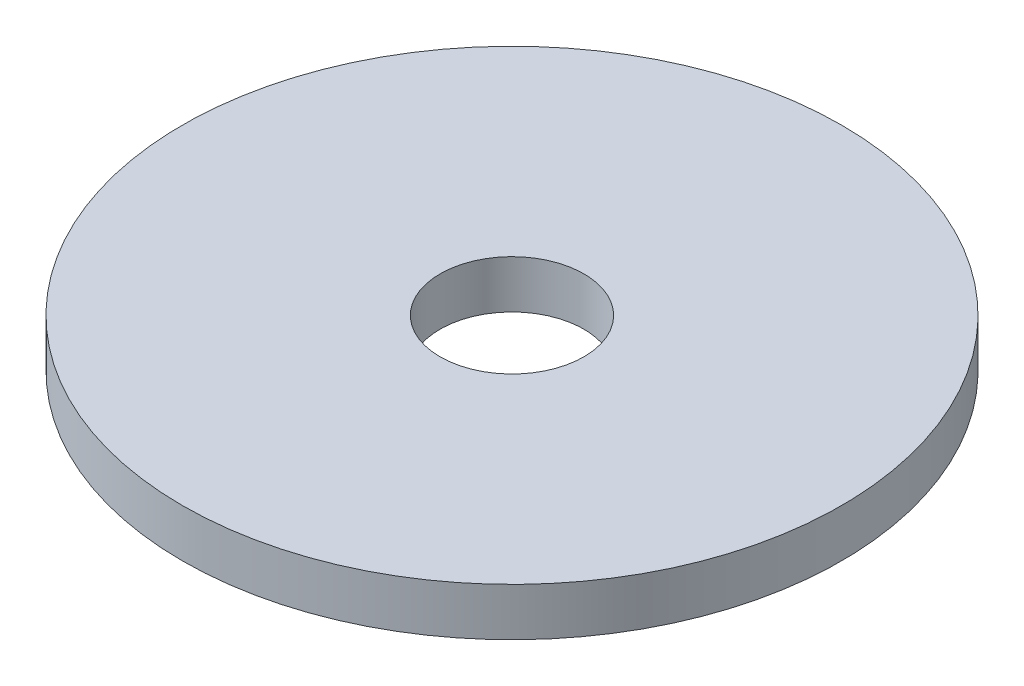
SolidWorks part; units mm, degrees
ref_plane "Front Plane" through (0, 0, 0) normal (0, 0, 1) x (1, 0, 0)
ref_plane "Top Plane" through (0, 0, 0) normal (0, 1, 0) x (1, 0, 0)
ref_plane "Right Plane" through (0, 0, 0) normal (1, 0, 0) x (0, 0, -1)
sketch "Sketch1" plane through (0, 0, 0) normal (0, 1, 0) x (1, 0, 0)
  circle A0 centre (0, 0) radius 27.5
  circle A1 centre (0, 0) radius 6
  dimension "D1" = 55
  dimension "D2" = 12
extrude "Boss-Extrude1" add sketch "Sketch1" along normal blind 4
sketch "Sketch2" plane through (0, 0, 0) normal (0, -1, 0) x (1, 0, 0)
  spline S0 degree 3 poles (783.5995, -748.4495) (32.8431, -47.3253) (88.3902, -17.4198) (93.8115, -26.7138) (93.9859, -27.5176) (93.9069, -28.333) (93.5786, -29.0907) (93.0307, -29.7103) (92.3264, -30.1263) (91.5328, -30.3082) (80.8051, -29.3947) (82.7854, 34.349) (1055.4923, -290.1326) knots -0.028735 -0.028735 -0.028735 -0.028735 0.000809 0.001618 0.002427 0.003235 0.004044 0.004853 0.005662 0.006471 0.00728 0.037205 0.037205 0.037205 0.037205 weights 1 1 1 1 1 1 1 1 1 1 1 1 1 only from (92.7348, -25.473) to (89.9615, -29.8717) construction
  spline S1 degree 3 poles (-600.9031, 693.1047) (149.8533, -8.0194) (94.3062, -37.925) (88.8848, -28.631) (88.7105, -27.8272) (88.7895, -27.0118) (89.1177, -26.254) (89.6657, -25.6344) (90.37, -25.2184) (91.1635, -25.0366) (101.8913, -25.95) (99.911, -89.6937) (-872.7959, 234.7879) knots -0.028735 -0.028735 -0.028735 -0.028735 0.000809 0.001618 0.002427 0.003235 0.004044 0.004853 0.005662 0.006471 0.00728 0.037205 0.037205 0.037205 0.037205 weights 1 1 1 1 1 1 1 1 1 1 1 1 1 only from (89.9615, -29.8717) to (92.7348, -25.473) construction
  spline S2 degree 3 poles (791.8718, -750.5841) (24.3799, -66.7142) (78.4052, -37.6563) (83.7379, -46.8377) (83.9102, -47.6464) (83.8268, -48.4628) (83.4968, -49.2142) (82.9576, -49.8227) (82.2624, -50.2396) (81.4531, -50.4267) (70.9451, -49.5095) (71.5543, 11.7618) (1054.8388, -272.393) knots -0.028153 -0.028153 -0.028153 -0.028153 0.000809 0.001618 0.002426 0.003235 0.004044 0.004853 0.005662 0.006471 0.007279 0.036703 0.036703 0.036703 0.036703 weights 1 1 1 1 1 1 1 1 1 1 1 1 1 only from (82.6582, -45.5904) to (79.8848, -49.9891) construction
  spline S3 degree 3 poles (-629.3288, 655.0045) (138.1631, -28.8654) (84.1378, -57.9233) (78.8051, -48.7419) (78.6328, -47.9332) (78.7162, -47.1167) (79.0462, -46.3654) (79.5854, -45.7569) (80.2806, -45.34) (81.0899, -45.1529) (91.5979, -46.0701) (90.9887, -107.3414) (-892.2958, 176.8135) knots -0.028153 -0.028153 -0.028153 -0.028153 0.000809 0.001618 0.002426 0.003235 0.004044 0.004853 0.005662 0.006471 0.007279 0.036703 0.036703 0.036703 0.036703 weights 1 1 1 1 1 1 1 1 1 1 1 1 1 only from (79.8848, -49.9891) to (82.6582, -45.5904) construction
  spline S4 degree 3 poles (-598.596, 654.2019) (152.1604, -46.9222) (96.6134, -76.8278) (91.192, -67.5338) (91.0177, -66.73) (91.0967, -65.9146) (91.4249, -65.1568) (91.9729, -64.5372) (92.6772, -64.1212) (93.4707, -63.9394) (104.1984, -64.8528) (102.2181, -128.5965) (-870.4887, 195.8851) knots -0.028735 -0.028735 -0.028735 -0.028735 0.000809 0.001618 0.002427 0.003235 0.004044 0.004853 0.005662 0.006471 0.00728 0.037205 0.037205 0.037205 0.037205 weights 1 1 1 1 1 1 1 1 1 1 1 1 1 only from (92.2687, -68.7745) to (95.042, -64.3758) construction
  spline S5 degree 3 poles (785.9067, -787.3522) (35.1503, -86.2281) (90.6973, -56.3225) (96.1187, -65.6166) (96.2931, -66.4204) (96.214, -67.2358) (95.8858, -67.9935) (95.3378, -68.6131) (94.6335, -69.0291) (93.84, -69.211) (83.1123, -68.2975) (85.0926, -4.5538) (1057.7994, -329.0354) knots -0.028735 -0.028735 -0.028735 -0.028735 0.000809 0.001618 0.002427 0.003235 0.004044 0.004853 0.005662 0.006471 0.00728 0.037205 0.037205 0.037205 0.037205 weights 1 1 1 1 1 1 1 1 1 1 1 1 1 only from (95.042, -64.3758) to (92.2687, -68.7745) construction
  spline S6 degree 3 poles (805.7524, -788.5108) (55.2705, -87.2378) (112.9894, -54.729) (118.579, -64.2831) (118.7534, -65.0889) (118.6754, -65.9009) (118.3456, -66.6633) (117.797, -67.2821) (117.0927, -67.6976) (116.2996, -67.8789) (105.571, -66.9633) (107.474, -3.1589) (1081.3265, -323.7381) knots -0.0296 -0.0296 -0.0296 -0.0296 0.000809 0.001618 0.002426 0.003235 0.004044 0.004853 0.005662 0.00647 0.007279 0.037234 0.037234 0.037234 0.037234 weights 1 1 1 1 1 1 1 1 1 1 1 1 1 only from (117.5026, -63.0438) to (114.7292, -67.4425) construction
  spline S7 degree 3 poles (-573.5206, 658.0246) (176.9613, -43.2484) (119.2424, -75.7573) (113.6527, -66.2031) (113.4784, -65.3973) (113.5564, -64.5854) (113.8861, -63.8229) (114.4348, -63.2041) (115.1391, -62.7886) (115.9322, -62.6073) (126.6608, -63.5229) (124.7578, -127.3273) (-849.0948, 193.2519) knots -0.0296 -0.0296 -0.0296 -0.0296 0.000809 0.001618 0.002426 0.003235 0.004044 0.004853 0.005662 0.00647 0.007279 0.037234 0.037234 0.037234 0.037234 weights 1 1 1 1 1 1 1 1 1 1 1 1 1 only from (114.7292, -67.4425) to (117.5026, -63.0438) construction
  spline S8 degree 3 poles (-566.0587, 675.6514) (184.6977, -25.4728) (129.1506, -55.3783) (123.7292, -46.0843) (123.5549, -45.2805) (123.6339, -44.4651) (123.9621, -43.7073) (124.5101, -43.0877) (125.2144, -42.6717) (126.0079, -42.4899) (136.7357, -43.4034) (134.7553, -107.147) (-837.9515, 217.3346) knots -0.028735 -0.028735 -0.028735 -0.028735 0.000809 0.001618 0.002427 0.003235 0.004044 0.004853 0.005662 0.006471 0.00728 0.037205 0.037205 0.037205 0.037205 weights 1 1 1 1 1 1 1 1 1 1 1 1 1 only from (124.8059, -47.325) to (127.5792, -42.9263) construction
  spline S9 degree 3 poles (818.4439, -765.9028) (67.6875, -64.7786) (123.2345, -34.8731) (128.6559, -44.1671) (128.8303, -44.9709) (128.7513, -45.7863) (128.423, -46.544) (127.8751, -47.1636) (127.1708, -47.5797) (126.3772, -47.7615) (115.6495, -46.848) (117.6298, 16.8956) (1090.3367, -307.5859) knots -0.028735 -0.028735 -0.028735 -0.028735 0.000809 0.001618 0.002427 0.003235 0.004044 0.004853 0.005662 0.006471 0.00728 0.037205 0.037205 0.037205 0.037205 weights 1 1 1 1 1 1 1 1 1 1 1 1 1 only from (127.5792, -42.9263) to (124.8059, -47.325) construction
  spline S10 degree 3 poles (-578.4426, 694.4368) (172.3138, -6.6874) (116.7667, -36.5929) (111.3453, -27.2989) (111.171, -26.4951) (111.25, -25.6797) (111.5783, -24.922) (112.1262, -24.3024) (112.8305, -23.8864) (113.6241, -23.7045) (124.3518, -24.618) (122.3715, -88.3617) (-850.3354, 236.1199) knots -0.028735 -0.028735 -0.028735 -0.028735 0.000809 0.001618 0.002427 0.003235 0.004044 0.004853 0.005662 0.006471 0.00728 0.037205 0.037205 0.037205 0.037205 weights 1 1 1 1 1 1 1 1 1 1 1 1 1 only from (112.422, -28.5397) to (115.1954, -24.141) construction
  spline S11 degree 3 poles (806.06, -747.1174) (55.3036, -45.9933) (110.8507, -16.0877) (116.2721, -25.3817) (116.4464, -26.1855) (116.3674, -27.0009) (116.0392, -27.7587) (115.4912, -28.3783) (114.7869, -28.7943) (113.9933, -28.9761) (103.2656, -28.0627) (105.2459, 35.681) (1077.9528, -288.8006) knots -0.028735 -0.028735 -0.028735 -0.028735 0.000809 0.001618 0.002427 0.003235 0.004044 0.004853 0.005662 0.006471 0.00728 0.037205 0.037205 0.037205 0.037205 weights 1 1 1 1 1 1 1 1 1 1 1 1 1 only from (115.1954, -24.141) to (112.422, -28.5397) construction
  spline S12 degree 3 poles (92.7348, -25.473) (92.9652, -25.6182) (93.3894, -25.9901) (93.8115, -26.7138) (93.9859, -27.5176) (93.9069, -28.333) (93.5786, -29.0907) (93.0307, -29.7103) (92.3264, -30.1263) (91.5328, -30.3082) (90.7075, -30.2379) (90.1918, -30.0169) (89.9615, -29.8717) knots 0 0 0 0 0.000809 0.001618 0.002427 0.003235 0.004044 0.004853 0.005662 0.006471 0.00728 0.008088 0.008088 0.008088 0.008088 weights 1 1 1 1 1 1 1 1 1 1 1 1 1
  spline S13 degree 3 poles (89.9615, -29.8717) (89.7312, -29.7265) (89.307, -29.3547) (88.8848, -28.631) (88.7105, -27.8272) (88.7895, -27.0118) (89.1177, -26.254) (89.6657, -25.6344) (90.37, -25.2184) (91.1635, -25.0366) (91.9888, -25.1068) (92.5045, -25.3278) (92.7348, -25.473) knots 0 0 0 0 0.000809 0.001618 0.002427 0.003235 0.004044 0.004853 0.005662 0.006471 0.00728 0.008088 0.008088 0.008088 0.008088 weights 1 1 1 1 1 1 1 1 1 1 1 1 1
  spline S14 degree 3 poles (82.6582, -45.5904) (82.8885, -45.7357) (83.3148, -46.1092) (83.7379, -46.8377) (83.9102, -47.6464) (83.8268, -48.4628) (83.4968, -49.2142) (82.9576, -49.8227) (82.2624, -50.2396) (81.4531, -50.4267) (80.6317, -50.355) (80.1151, -50.1344) (79.8848, -49.9891) knots 0 0 0 0 0.000809 0.001618 0.002426 0.003235 0.004044 0.004853 0.005662 0.006471 0.007279 0.008088 0.008088 0.008088 0.008088 weights 1 1 1 1 1 1 1 1 1 1 1 1 1
  spline S15 degree 3 poles (79.8848, -49.9891) (79.6545, -49.8439) (79.2282, -49.4704) (78.8051, -48.7419) (78.6328, -47.9332) (78.7162, -47.1167) (79.0462, -46.3654) (79.5854, -45.7569) (80.2806, -45.34) (81.0899, -45.1529) (81.9113, -45.2246) (82.4278, -45.4452) (82.6582, -45.5904) knots 0 0 0 0 0.000809 0.001618 0.002426 0.003235 0.004044 0.004853 0.005662 0.006471 0.007279 0.008088 0.008088 0.008088 0.008088 weights 1 1 1 1 1 1 1 1 1 1 1 1 1
  spline S16 degree 3 poles (92.2687, -68.7745) (92.0384, -68.6293) (91.6141, -68.2575) (91.192, -67.5338) (91.0177, -66.73) (91.0967, -65.9146) (91.4249, -65.1568) (91.9729, -64.5372) (92.6772, -64.1212) (93.4707, -63.9394) (94.296, -64.0096) (94.8117, -64.2306) (95.042, -64.3758) knots 0 0 0 0 0.000809 0.001618 0.002427 0.003235 0.004044 0.004853 0.005662 0.006471 0.00728 0.008088 0.008088 0.008088 0.008088 weights 1 1 1 1 1 1 1 1 1 1 1 1 1
  spline S17 degree 3 poles (95.042, -64.3758) (95.2723, -64.521) (95.6966, -64.8928) (96.1187, -65.6166) (96.2931, -66.4204) (96.214, -67.2358) (95.8858, -67.9935) (95.3378, -68.6131) (94.6335, -69.0291) (93.84, -69.211) (93.0147, -69.1407) (92.499, -68.9197) (92.2687, -68.7745) knots 0 0 0 0 0.000809 0.001618 0.002427 0.003235 0.004044 0.004853 0.005662 0.006471 0.00728 0.008088 0.008088 0.008088 0.008088 weights 1 1 1 1 1 1 1 1 1 1 1 1 1
  spline S18 degree 3 poles (117.5026, -63.0438) (117.7329, -63.189) (118.1556, -63.5593) (118.579, -64.2831) (118.7534, -65.0889) (118.6754, -65.9009) (118.3456, -66.6633) (117.797, -67.2821) (117.0927, -67.6976) (116.2996, -67.8789) (115.4751, -67.8085) (114.9595, -67.5877) (114.7292, -67.4425) knots 0 0 0 0 0.000809 0.001618 0.002426 0.003235 0.004044 0.004853 0.005662 0.00647 0.007279 0.008088 0.008088 0.008088 0.008088 weights 1 1 1 1 1 1 1 1 1 1 1 1 1
  spline S19 degree 3 poles (114.7292, -67.4425) (114.4989, -67.2973) (114.0762, -66.927) (113.6527, -66.2031) (113.4784, -65.3973) (113.5564, -64.5854) (113.8861, -63.8229) (114.4348, -63.2041) (115.1391, -62.7886) (115.9322, -62.6073) (116.7567, -62.6777) (117.2722, -62.8986) (117.5026, -63.0438) knots 0 0 0 0 0.000809 0.001618 0.002426 0.003235 0.004044 0.004853 0.005662 0.00647 0.007279 0.008088 0.008088 0.008088 0.008088 weights 1 1 1 1 1 1 1 1 1 1 1 1 1
  spline S20 degree 3 poles (124.8059, -47.325) (124.5756, -47.1798) (124.1514, -46.808) (123.7292, -46.0843) (123.5549, -45.2805) (123.6339, -44.4651) (123.9621, -43.7073) (124.5101, -43.0877) (125.2144, -42.6717) (126.0079, -42.4899) (126.8332, -42.5602) (127.3489, -42.7811) (127.5792, -42.9263) knots 0 0 0 0 0.000809 0.001618 0.002427 0.003235 0.004044 0.004853 0.005662 0.006471 0.00728 0.008088 0.008088 0.008088 0.008088 weights 1 1 1 1 1 1 1 1 1 1 1 1 1
  spline S21 degree 3 poles (127.5792, -42.9263) (127.8095, -43.0716) (128.2338, -43.4434) (128.6559, -44.1671) (128.8303, -44.9709) (128.7513, -45.7863) (128.423, -46.544) (127.8751, -47.1636) (127.1708, -47.5797) (126.3772, -47.7615) (125.5519, -47.6912) (125.0362, -47.4703) (124.8059, -47.325) knots 0 0 0 0 0.000809 0.001618 0.002427 0.003235 0.004044 0.004853 0.005662 0.006471 0.00728 0.008088 0.008088 0.008088 0.008088 weights 1 1 1 1 1 1 1 1 1 1 1 1 1
  spline S22 degree 3 poles (112.422, -28.5397) (112.1917, -28.3945) (111.7675, -28.0226) (111.3453, -27.2989) (111.171, -26.4951) (111.25, -25.6797) (111.5783, -24.922) (112.1262, -24.3024) (112.8305, -23.8864) (113.6241, -23.7045) (114.4493, -23.7748) (114.9651, -23.9958) (115.1954, -24.141) knots 0 0 0 0 0.000809 0.001618 0.002427 0.003235 0.004044 0.004853 0.005662 0.006471 0.00728 0.008088 0.008088 0.008088 0.008088 weights 1 1 1 1 1 1 1 1 1 1 1 1 1
  spline S23 degree 3 poles (115.1954, -24.141) (115.4257, -24.2862) (115.8499, -24.658) (116.2721, -25.3817) (116.4464, -26.1855) (116.3674, -27.0009) (116.0392, -27.7587) (115.4912, -28.3783) (114.7869, -28.7943) (113.9933, -28.9761) (113.1681, -28.9059) (112.6524, -28.6849) (112.422, -28.5397) knots 0 0 0 0 0.000809 0.001618 0.002427 0.003235 0.004044 0.004853 0.005662 0.006471 0.00728 0.008088 0.008088 0.008088 0.008088 weights 1 1 1 1 1 1 1 1 1 1 1 1 1
extrude "Cut-Extrude1" cut sketch "Sketch2" against normal through all
